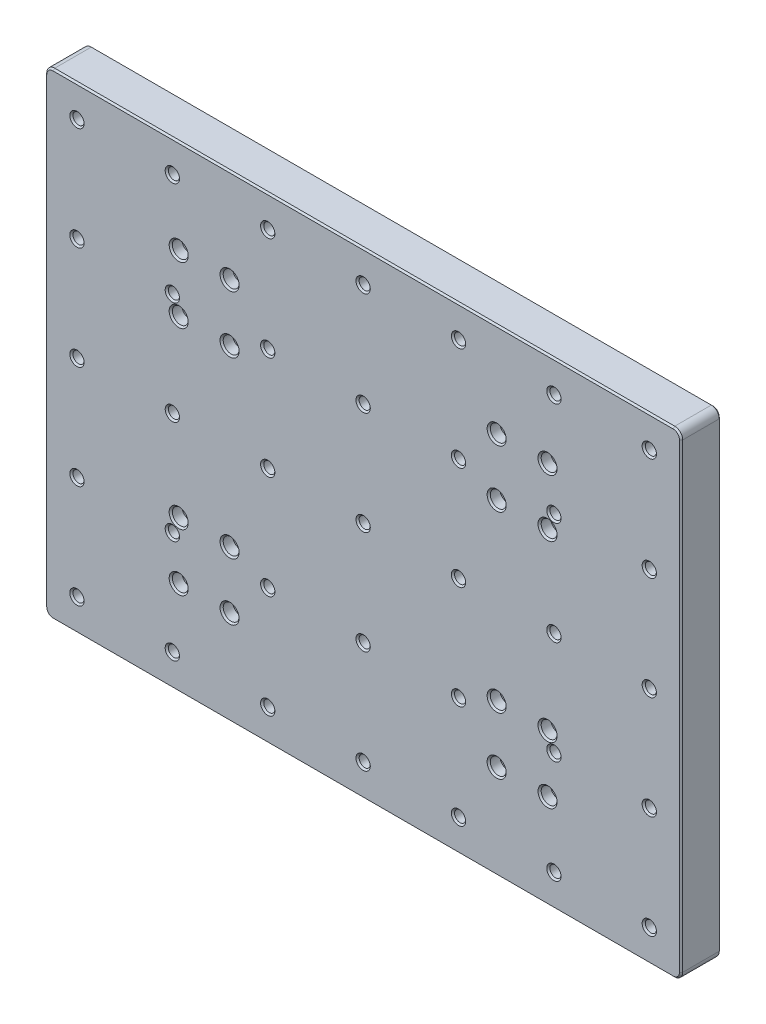
SolidWorks part; units mm, degrees
ref_plane "Front Plane" through (0, 0, 0) normal (0, 0, 1) x (1, 0, 0)
ref_plane "Top Plane" through (0, 0, 0) normal (0, 1, 0) x (1, 0, 0)
ref_plane "Right Plane" through (0, 0, 0) normal (1, 0, 0) x (0, 0, -1)
sketch "Sketch1" plane through (0, 0, 0) normal (0, 0, 1) x (1, 0, 0)
  line L1 (-200, 150) -> (200, 150)
  line L2 (-200, 150) -> (-200, -150)
  line L3 (-200, -150) -> (200, -150)
  line L4 (200, 150) -> (200, -150)
  line L5 (0, -150) -> (0, 150) construction
  line L6 (-200, 0) -> (200, 0) construction
  point P0 (0, 0)
  dimension "D1" = 300
  dimension "D2" = 400
extrude "Boss-Extrude1" add sketch "Sketch1" along normal blind 25
sketch "Sketch3" plane through (0, 0, 25) normal (0, 0, 1) x (1, 0, 0)
  circle A0 centre (-116, 90.75) radius 5
  circle A1 centre (-84, 90.75) radius 5
  circle A2 centre (-116, 54.75) radius 5
  circle A3 centre (-84, 54.75) radius 5
  circle A4 centre (84, 90.75) radius 5
  circle A5 centre (116, 90.75) radius 5
  circle A6 centre (84, 54.75) radius 5
  circle A7 centre (116, 54.75) radius 5
  circle A8 centre (116, -54.75) radius 5
  circle A9 centre (84, -54.75) radius 5
  circle A10 centre (84, -90.75) radius 5
  circle A11 centre (116, -90.75) radius 5
  circle A12 centre (-84, -90.75) radius 5
  circle A13 centre (-116, -90.75) radius 5
  circle A14 centre (-116, -54.75) radius 5
  circle A15 centre (-84, -54.75) radius 5
hole_wizard "CBORE for M5 SHCS1" positions "3DSketch2" profile "Sketch4" counterbore size "M5" standard "ANSI Metric"
sketch3d "3DSketch2"
  point P0 (-116, 90.75, 25)
  point P3 (-84, 90.75, 25)
  point P6 (-116, 54.75, 25)
  point P9 (-84, 54.75, 25)
  point P17 (-116, -54.75, 25)
  point P22 (-84, -54.75, 25)
  point P25 (-116, -90.75, 25)
  point P28 (-84, -90.75, 25)
  point P31 (116, -90.75, 25)
  point P34 (84, -90.75, 25)
  point P37 (84, -54.75, 25)
  point P40 (116, -54.75, 25)
  point P43 (84, 90.75, 25)
  point P46 (116, 90.75, 25)
  point P49 (84, 54.75, 25)
  point P52 (116, 54.75, 25)
sketch "Sketch4" plane through (-116, 90.75, 25) normal (1, 0, 0) x (0, -1, 0)
  line L0 (0, 0) -> (0, 30)
  line L1 (0, 30) -> (2.75, 28.3476)
  line L2 (2.75, 28.3476) -> (2.75, 7)
  line L3 (2.75, 7) -> (5, 7)
  line L4 (5, 7) -> (5, 0)
  line L5 (5, 0) -> (0, 0)
  line L10 (0, 30) -> (-2.75, 28.3476) construction
  line L11 (0, -6.35) -> (0, 107.95) construction
  dimension "Hole Dia." = 5.5
  dimension "Hole Depth" = 30
  dimension "C'Bore Dia." = 10
  dimension "C'Bore Depth" = 7
  dimension "Drill Angle" = 118
fillet "Fillet1" radius 5 4 edges at (200, 150, 12.5) (200, -150, 12.5) (-200, -150, 12.5) (-200, 150, 12.5)
sketch "Sketch5" plane through (0, 0, 25) normal (0, 0, 1) x (1, 0, 0)
  circle A40 centre (-180, 130) radius 3.5
  circle A41 centre (-120, 130) radius 3.5
  circle A42 centre (-60, 130) radius 3.5
  circle A43 centre (0, 130) radius 3.5
  circle A44 centre (60, 130) radius 3.5
  circle A45 centre (120, 130) radius 3.5
  circle A46 centre (180, 130) radius 3.5
  circle A47 centre (-120, 65) radius 3.5
  circle A48 centre (-60, 65) radius 3.5
  circle A49 centre (0, 65) radius 3.5
  circle A50 centre (60, 65) radius 3.5
  circle A51 centre (120, 65) radius 3.5
  circle A52 centre (180, 65) radius 3.5
  circle A53 centre (-120, 0) radius 3.5
  circle A54 centre (-60, 0) radius 3.5
  circle A55 centre (0, 0) radius 3.5
  circle A56 centre (60, 0) radius 3.5
  circle A57 centre (120, 0) radius 3.5
  circle A58 centre (180, 0) radius 3.5
  circle A59 centre (-120, -65) radius 3.5
  circle A60 centre (-60, -65) radius 3.5
  circle A61 centre (0, -65) radius 3.5
  circle A62 centre (60, -65) radius 3.5
  circle A63 centre (120, -65) radius 3.5
  circle A64 centre (180, -65) radius 3.5
  circle A65 centre (-120, -130) radius 3.5
  circle A66 centre (-60, -130) radius 3.5
  circle A67 centre (0, -130) radius 3.5
  circle A68 centre (60, -130) radius 3.5
  circle A69 centre (120, -130) radius 3.5
  circle A70 centre (180, -130) radius 3.5
  circle A71 centre (-180, 65) radius 3.5
  circle A72 centre (-180, 0) radius 3.5
  circle A73 centre (-180, -65) radius 3.5
  circle A74 centre (-180, -130) radius 3.5
  dimension "D1" = 7
  dimension "D2" = 5
extrude "Cut-Extrude2" cut sketch "Sketch5" against normal through all
chamfer "Chamfer1" distance 1 angle 45 59 edges at (198.5355, -148.5355, 25) (0, -150, 25) (-198.5355, -148.5355, 25) (-200, 0, 25) (-198.5355, 148.5355, 25) (0, 150, 25) (198.5355, 148.5355, 25) (200, 0, 25) (121, 54.75, 25) (89, 54.75, 25) (121, 90.75, 25) (89, 90.75, 25) (121, -54.75, 25) (89, -54.75, 25) (89, -90.75, 25) (121, -90.75, 25) (-79, -90.75, 25) (-111, -90.75, 25) (-79, -54.75, 25) (-111, -54.75, 25) (-79, 54.75, 25) (-111, 54.75, 25) (-79, 90.75, 25) (-111, 90.75, 25) (-176.5, 130, 25) (-176.5, -130, 25) (-176.5, -65, 25) (63.5, 0, 25) (3.5, 0, 25) (-56.5, 0, 25) (-116.5, 0, 25) (183.5, 65, 25) (123.5, 65, 25) (63.5, 65, 25) (3.5, 65, 25) (-116.5, 130, 25) (-56.5, 130, 25) (3.5, 130, 25) (63.5, 130, 25) (123.5, 130, 25) (183.5, 130, 25) (-116.5, 65, 25) (-56.5, 65, 25) (-116.5, -130, 25) (-56.5, -130, 25) (3.5, -130, 25) (63.5, -130, 25) (123.5, -130, 25) (183.5, -130, 25) (-176.5, 65, 25) (-176.5, 0, 25) (123.5, 0, 25) (183.5, 0, 25) (-116.5, -65, 25) (-56.5, -65, 25) (3.5, -65, 25) (63.5, -65, 25) (123.5, -65, 25) (183.5, -65, 25)
chamfer "Chamfer2" distance 1 angle 45 59 edges at (-198.5355, 148.5355, 0) (-200, 0, 0) (-198.5355, -148.5355, 0) (0, -150, 0) (198.5355, -148.5355, 0) (200, 0, 0) (198.5355, 148.5355, 0) (0, 150, 0) (118.75, 54.75, 0) (86.75, 54.75, 0) (118.75, 90.75, 0) (86.75, 90.75, 0) (118.75, -54.75, 0) (86.75, -54.75, 0) (86.75, -90.75, 0) (118.75, -90.75, 0) (-81.25, -90.75, 0) (-113.25, -90.75, 0) (-81.25, -54.75, 0) (-113.25, -54.75, 0) (-81.25, 54.75, 0) (-113.25, 54.75, 0) (-81.25, 90.75, 0) (-113.25, 90.75, 0) (-176.5, 130, 0) (-176.5, -130, 0) (-176.5, -65, 0) (63.5, 0, 0) (3.5, 0, 0) (-56.5, 0, 0) (-116.5, 0, 0) (183.5, 65, 0) (123.5, 65, 0) (63.5, 65, 0) (3.5, 65, 0) (-116.5, 130, 0) (-56.5, 130, 0) (3.5, 130, 0) (63.5, 130, 0) (123.5, 130, 0) (183.5, 130, 0) (-116.5, 65, 0) (-56.5, 65, 0) (-116.5, -130, 0) (-56.5, -130, 0) (3.5, -130, 0) (63.5, -130, 0) (123.5, -130, 0) (183.5, -130, 0) (-176.5, 65, 0) (-176.5, 0, 0) (123.5, 0, 0) (183.5, 0, 0) (-116.5, -65, 0) (-56.5, -65, 0) (3.5, -65, 0) (63.5, -65, 0) (123.5, -65, 0) (183.5, -65, 0)
